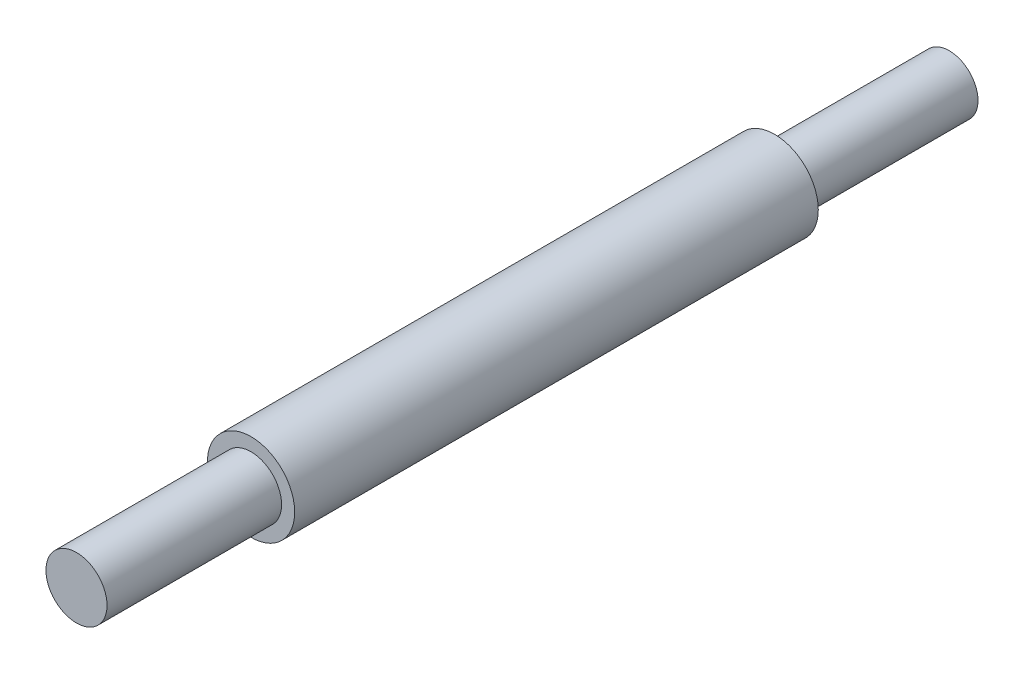
SolidWorks part; units mm, degrees
ref_plane "前视基准面" through (0, 0, 0) normal (0, 0, 1) x (1, 0, 0)
ref_plane "上视基准面" through (0, 0, 0) normal (0, 1, 0) x (1, 0, 0)
ref_plane "右视基准面" through (0, 0, 0) normal (1, 0, 0) x (0, 0, -1)
sketch "草图1" plane through (0, 0, 0) normal (0, 0, 1) x (1, 0, 0)
  circle A0 centre (0, 0) radius 1.65
extrude "凸台-拉伸1" add sketch "草图1" along normal blind 10
sketch "草图2" plane through (0, 0, 10) normal (0, 0, 1) x (1, 0, 0)
  circle A0 centre (0, 0) radius 2.5
  dimension "D1" = 5
extrude "凸台-拉伸2" add sketch "草图2" along normal blind 30
sketch "草图3" plane through (0, 0, 40) normal (0, 0, 1) x (1, 0, 0)
  circle A0 centre (0, 0) radius 1.75
extrude "凸台-拉伸3" add sketch "草图3" along normal blind 10
